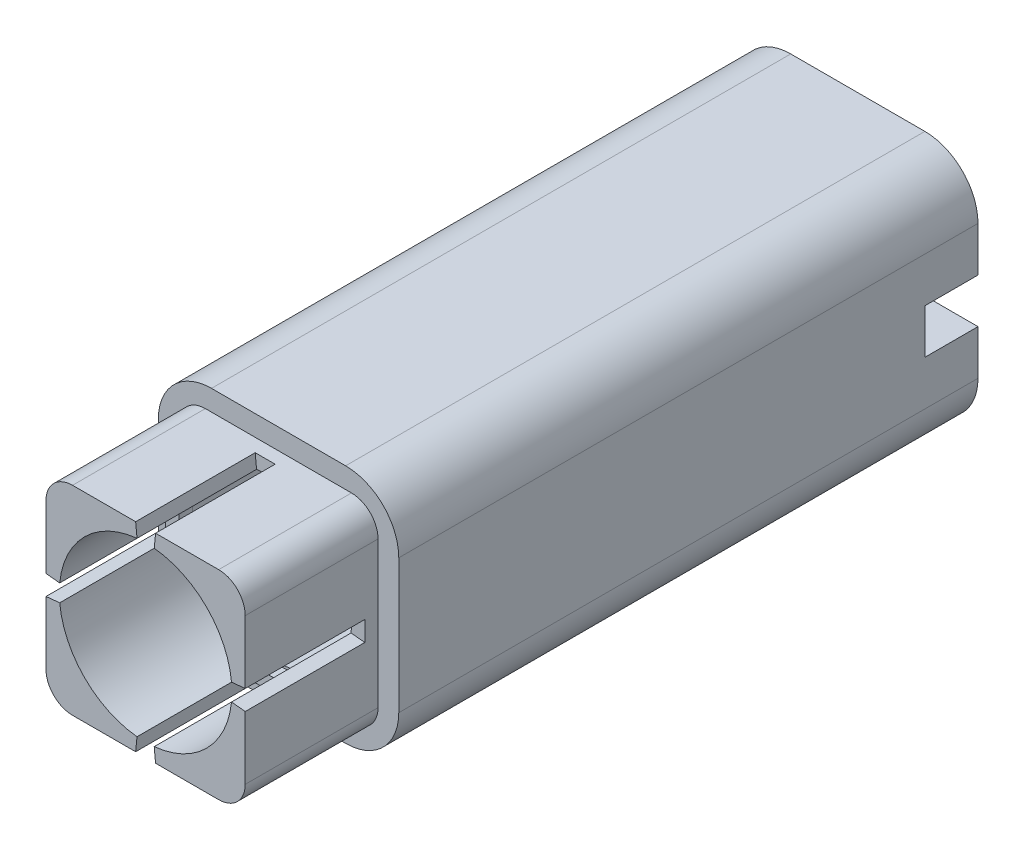
SolidWorks part; units mm, degrees
ref_plane "Front Plane" through (0, 0, 0) normal (0, 0, 1) x (1, 0, 0)
ref_plane "Top Plane" through (0, 0, 0) normal (0, 1, 0) x (1, 0, 0)
ref_plane "Right Plane" through (0, 0, 0) normal (1, 0, 0) x (0, 0, -1)
sketch "Sketch1" plane through (0, 0, 0) normal (0, 0, 1) x (1, 0, 0)
  line L0 (-5.05, 9.05) -> (5.05, 9.05)
  line L1 (9.05, -5.05) -> (9.05, 5.05)
  line L2 (0, 0) -> (0, 14.1446) construction
  line L3 (-9.05, -5.05) -> (-9.05, 5.05)
  line L4 (-12.732, 0) -> (15.0845, 0) construction
  line L5 (-5.05, -9.05) -> (5.05, -9.05)
  arc A4 (5.05, 9.05) -> (9.05, 5.05) centre (5.05, 5.05) cw
  arc A5 (9.05, -5.05) -> (5.05, -9.05) centre (5.05, -5.05) cw
  arc A6 (-5.05, -9.05) -> (-9.05, -5.05) centre (-5.05, -5.05) cw
  arc A7 (-9.05, 5.05) -> (-5.05, 9.05) centre (-5.05, 5.05) cw
  point P11 (9.05, 0)
  point P12 (0, 9.05)
  point P20 (0, -9.05)
  point P21 (-9.05, 0)
  dimension "D3" = 0
  dimension "D1" = 5.05
  dimension "D2" = 5.05
  dimension "D4" = 9.05
  dimension "D5" = 9.05
extrude "Boss-Extrude1" add sketch "Sketch1" along normal blind 43.61
sketch "Sketch3" plane through (0, 0, 43.61) normal (0, 0, 1) x (1, 0, 0)
  line L0 (-5.5091, -7.4997) -> (5.4909, -7.4997)
  line L1 (-7.5091, -5.4997) -> (-7.5091, 5.5003)
  line L2 (-5.5091, 7.5003) -> (5.4909, 7.5003)
  line L3 (7.4909, -5.4997) -> (7.4909, 5.5003)
  line L4 (-7.5091, -7.4997) -> (7.4909, 7.5003) construction
  line L5 (-7.5091, 7.5003) -> (7.4909, -7.4997) construction
  arc A2 (-5.5091, -7.4997) -> (-7.5091, -5.4997) centre (-5.5091, -5.4997) cw
  arc A3 (5.4909, -7.4997) -> (7.4909, -5.4997) centre (5.4909, -5.4997) ccw
  arc A4 (5.4909, 7.5003) -> (7.4909, 5.5003) centre (5.4909, 5.5003) cw
  arc A5 (-7.5091, 5.5003) -> (-5.5091, 7.5003) centre (-5.5091, 5.5003) cw
  circle A6 centre (-0.0091, 0.0003) radius 6.5
  point P3 (-0.0091, 0.0003)
  dimension "D1" = 15
  dimension "D2" = 2
  dimension "D3" = 13
  dimension "D4" = 0
extrude "Boss-Extrude2" add sketch "Sketch3" along normal blind 10
sketch "Sketch6" plane through (0, 0, 0) normal (0, 0, 1) x (1, 0, 0)
  line L0 (0, 3.3983) -> (0, -3.2292) construction
  line L2 (-2, -1.68) -> (2, -1.68)
  line L3 (-2, 1.68) -> (2, 1.68)
  line L7 (2, 1.68) -> (9.05, 1.68)
  line L8 (9.05, -5.05) -> (9.05, 5.05) construction
  line L9 (9.05, 1.68) -> (9.05, -1.68)
  line L10 (9.05, -1.68) -> (2, -1.68)
  arc A0 (-2, 1.68) -> (-2, -1.68) centre (-0.9148, 0) ccw
  point P3 (0, 1.9974)
  point P9 (0, -0.9026)
  dimension "D2" = 2
  dimension "D1" = 4
  dimension "D3" = 2
  dimension "D4" = 1.68
  dimension "D5" = 1.68
extrude "Cut-Extrude3" cut sketch "Sketch6" along normal blind 4
sketch "Sketch10" plane through (0, 0, 4) normal (0, 0, -1) x (-1, 0, 0)
  line L5 (-2.7, 1.68) -> (2, 1.68)
  line L6 (-9.05, 1.68) -> (2, 1.68) construction
  line L7 (-2.7, -1.68) -> (2, -1.68)
  line L8 (2, -1.68) -> (-9.05, -1.68) construction
  line L9 (-2.7, 1.68) -> (-2.7, -1.68)
  arc A0 (2, 1.68) -> (2, -1.68) centre (0.9148, 0) cw
  dimension "D1" = 4.7
extrude "Cut-Extrude6" cut sketch "Sketch10" against normal blind 2
sketch "Sketch11" plane through (0, 0, 53.61) normal (0, 0, 1) x (1, 0, 0)
  line L0 (0, 0) -> (7.4909, 0.75)
  line L1 (7.4909, -5.4997) -> (7.4909, 5.5003) construction
  line L2 (7.4909, 0.75) -> (7.4909, -0.75)
  line L3 (7.4909, -0.75) -> (0, 0)
  dimension "D1" = 0.75
  dimension "D2" = 0.75
extrude "Cut-Extrude7" cut sketch "Sketch11" against normal blind 9
pattern_circular "CirPattern1" count 4 over 360 about axis through (-0.0091, 0.0003, 0) along (0, 0, 1) of "Cut-Extrude7"
sketch "Sketch12" plane through (0, 0, 43.61) normal (0, 0, 1) x (1, 0, 0)
  line L0 (0, 0) -> (0, 14.1446) construction
  circle A0 centre (0, 0.1925) radius 6.5
  dimension "D1" = 13
extrude "Cut-Extrude8" cut sketch "Sketch12" against normal blind 37.61
